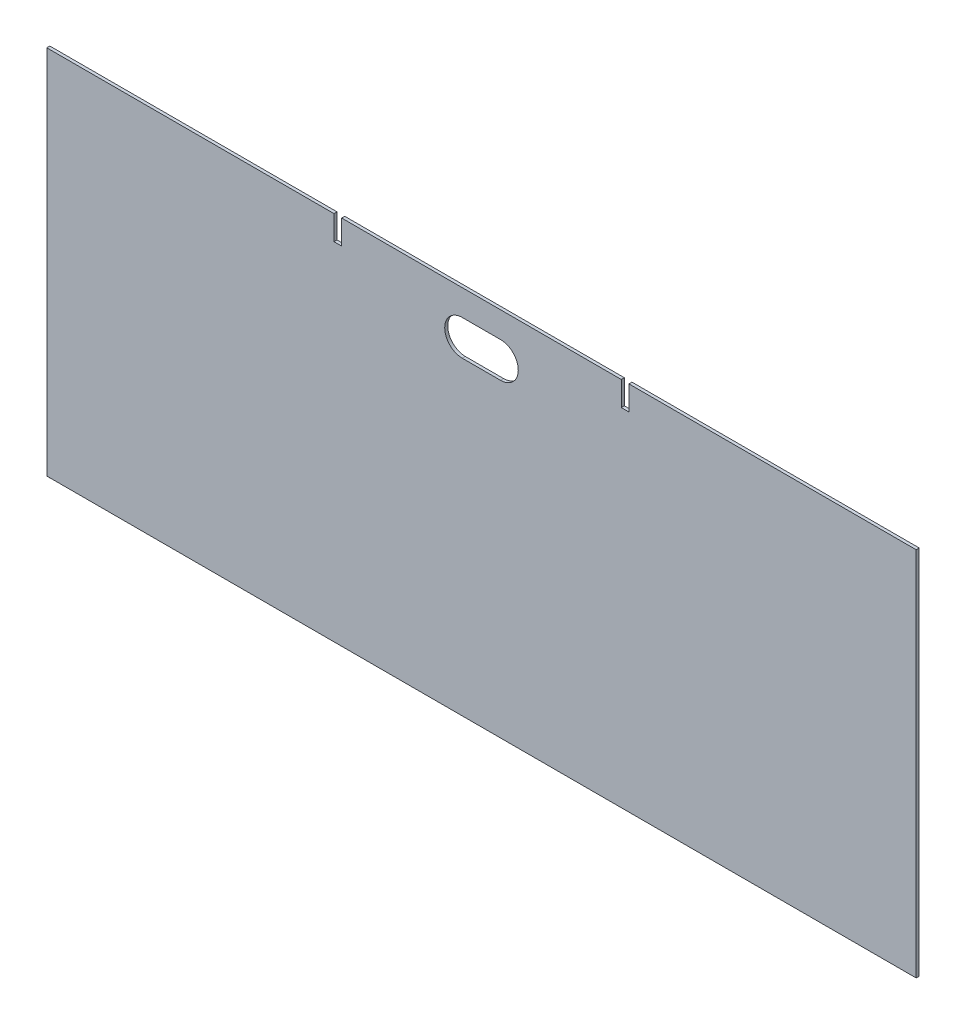
SolidWorks part; units mm, degrees
material "PC High Viscosity"
ref_plane "Front Plane" through (0, 0, 0) normal (0, 0, 1) x (1, 0, 0)
ref_plane "Top Plane" through (0, 0, 0) normal (0, 1, 0) x (1, 0, 0)
ref_plane "Right Plane" through (0, 0, 0) normal (1, 0, 0) x (0, 0, -1)
sketch "Sketch1" plane through (0, 0, 0) normal (0, 0, 1) x (1, 0, 0)
  line L1 (-908.05, 0) -> (908.05, 0)
  line L2 (-908.05, 0) -> (-908.05, 774.7)
  line L3 (-908.05, 774.7) -> (908.05, 774.7)
  line L4 (908.05, 0) -> (908.05, 774.7)
  dimension "D1" = 1816.1
  dimension "D2" = 774.7
extrude "base" add sketch "Sketch1" along normal blind 6.35
sketch "Sketch2" plane through (0, 0, 6.35) normal (0, 0, 1) x (1, 0, 0)
  line L0 (0, 85.2063) -> (0, 622.1305) construction
  line L1 (-307.975, 774.7) -> (-292.1, 774.7)
  line L2 (-307.975, 774.7) -> (-307.975, 723.9)
  line L3 (-307.975, 723.9) -> (-292.1, 723.9)
  line L4 (-292.1, 774.7) -> (-292.1, 723.9)
  line L5 (292.1, 774.7) -> (307.975, 774.7)
  line L6 (292.1, 774.7) -> (292.1, 723.9)
  line L7 (292.1, 723.9) -> (307.975, 723.9)
  line L8 (307.975, 774.7) -> (307.975, 723.9)
  line L9 (908.05, 774.7) -> (-908.05, 774.7) construction
  dimension "D1" = 584.2
  dimension "D2" = 50.8
  dimension "D3" = 15.875
extrude "rib-relief" cut sketch "Sketch2" against normal through all
sketch "Sketch3" plane through (0, 0, 6.35) normal (0, 0, 1) x (1, 0, 0)
  line L0 (-908.05, 0) -> (908.05, 0) construction
  line L1 (-80, 643.9) -> (80, 643.9) construction
  line L2 (-80, 643.9) -> (-80, 723.9) construction
  line L3 (-80, 723.9) -> (80, 723.9) construction
  line L4 (80, 643.9) -> (80, 723.9) construction
  line L5 (-80, 643.9) -> (80, 723.9) construction
  line L6 (-80, 723.9) -> (80, 643.9) construction
  line L7 (292.1, 774.7) -> (-292.1, 774.7) construction
  line L8 (-40, 683.9) -> (40, 683.9) construction
  line L9 (-40, 720.725) -> (40, 720.725)
  line L10 (-40, 647.075) -> (40, 647.075)
  arc A0 (-40, 720.725) -> (-40, 647.075) centre (-40, 683.9) ccw
  arc A1 (40, 647.075) -> (40, 720.725) centre (40, 683.9) ccw
  point P0 (0, 683.9)
  point P7 (0, 0)
  point P12 (0, 683.9)
  dimension "D5" = 3.175
  dimension "D6" = 3.175
  dimension "D1" = 160
  dimension "D2" = 80
  dimension "D3" = 50.8
  dimension "D4" = 3.175
extrude "cutout" cut sketch "Sketch3" against normal through all both and the other way through all
